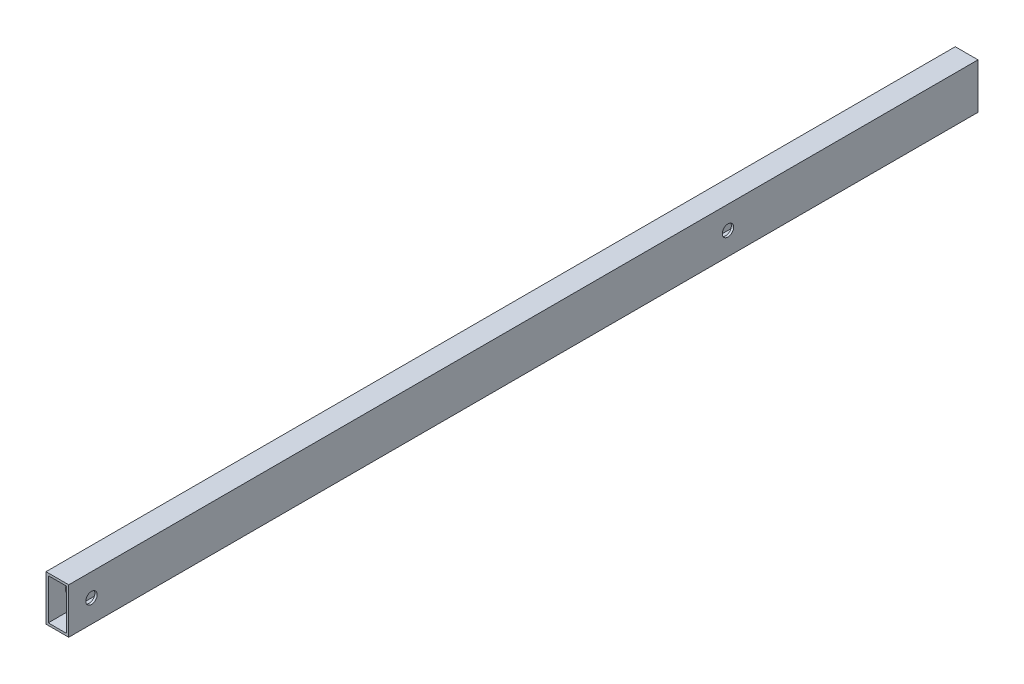
SolidWorks part; units mm, degrees
ref_plane "Front Plane" through (0, 0, 0) normal (0, 0, 1) x (1, 0, 0)
ref_plane "Top Plane" through (0, 0, 0) normal (0, 1, 0) x (1, 0, 0)
ref_plane "Right Plane" through (0, 0, 0) normal (1, 0, 0) x (0, 0, -1)
sketch "Sketch1" plane through (0, 0, 0) normal (0, 0, 1) x (1, 0, 0)
  line L0 (-4, -9) -> (4, -9)
  line L1 (-5, -10) -> (5, -10)
  line L2 (-5, -10) -> (-5, 10)
  line L3 (-5, 10) -> (5, 10)
  line L4 (5, -10) -> (5, 10)
  line L5 (-5, -10) -> (5, 10) construction
  line L6 (-5, 10) -> (5, -10) construction
  line L7 (4, -9) -> (4, 9)
  line L8 (-4, 9) -> (4, 9)
  line L9 (-4, -9) -> (-4, 9)
  point P0 (0, 0)
  dimension "D2" = 10
  dimension "D3" = 20
  dimension "D1" = 1
extrude "Boss-Extrude1" add sketch "Sketch1" along normal blind 400
sketch "Sketch2" plane through (5, 0, 0) normal (1, 0, 0) x (0, 0, -1)
  line L0 (0, 0) -> (-400, 0) construction
  line L1 (-400, -10) -> (-400, 10) construction
  circle A0 centre (-110, 0) radius 2.5
  circle A1 centre (-390, 0) radius 2.5
  dimension "D1" = 5
  dimension "D2" = 280
  dimension "D3" = 10
extrude "Cut-Extrude1" cut sketch "Sketch2" against normal through all
